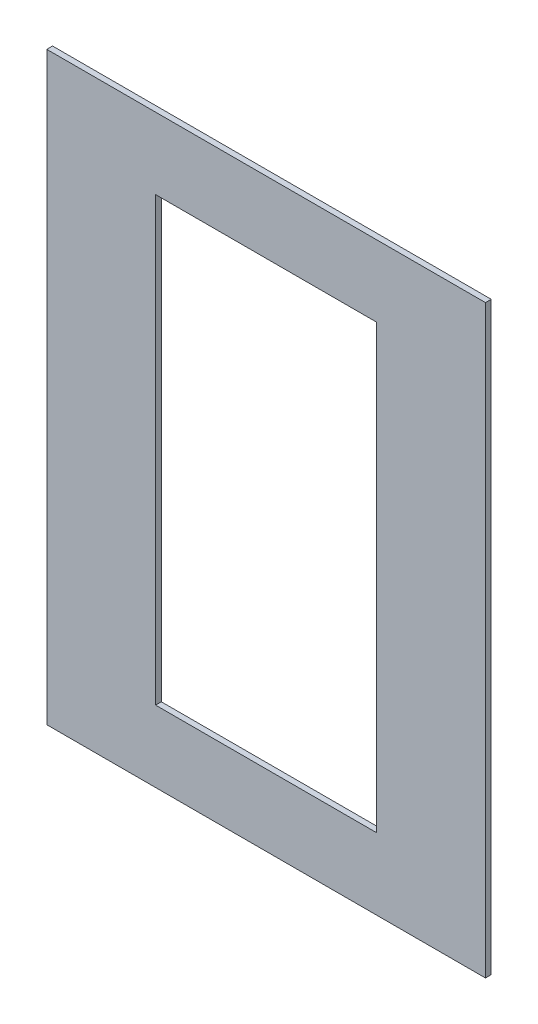
SolidWorks part; units mm, degrees
ref_plane "Front Plane" through (0, 0, 0) normal (0, 0, 1) x (1, 0, 0)
ref_plane "Top Plane" through (0, 0, 0) normal (0, 1, 0) x (1, 0, 0)
ref_plane "Right Plane" through (0, 0, 0) normal (1, 0, 0) x (0, 0, -1)
sketch "Sketch1" plane through (0, 0, 0) normal (0, 0, 1) x (1, 0, 0)
  line L1 (0, 0) -> (381, 0)
  line L2 (0, 0) -> (0, 508)
  line L3 (0, 508) -> (381, 508)
  line L4 (381, 0) -> (381, 508)
  dimension "D1" = 381
  dimension "D2" = 508
extrude "Boss-Extrude1" add sketch "Sketch1" along normal blind 5
sketch "Sketch2" plane through (0, 0, 5) normal (0, 0, 1) x (1, 0, 0)
  line L0 (0, 508) -> (0, 0) construction
  line L1 (94.5, 446) -> (286.5, 446)
  line L2 (94.5, 446) -> (94.5, 62)
  line L3 (94.5, 62) -> (286.5, 62)
  line L4 (286.5, 446) -> (286.5, 62)
  line L5 (381, 508) -> (0, 508) construction
  dimension "D1" = 94.5
  dimension "D2" = 62
  dimension "D3" = 192
  dimension "D4" = 384
extrude "Cut-Extrude1" cut sketch "Sketch2" against normal through all
